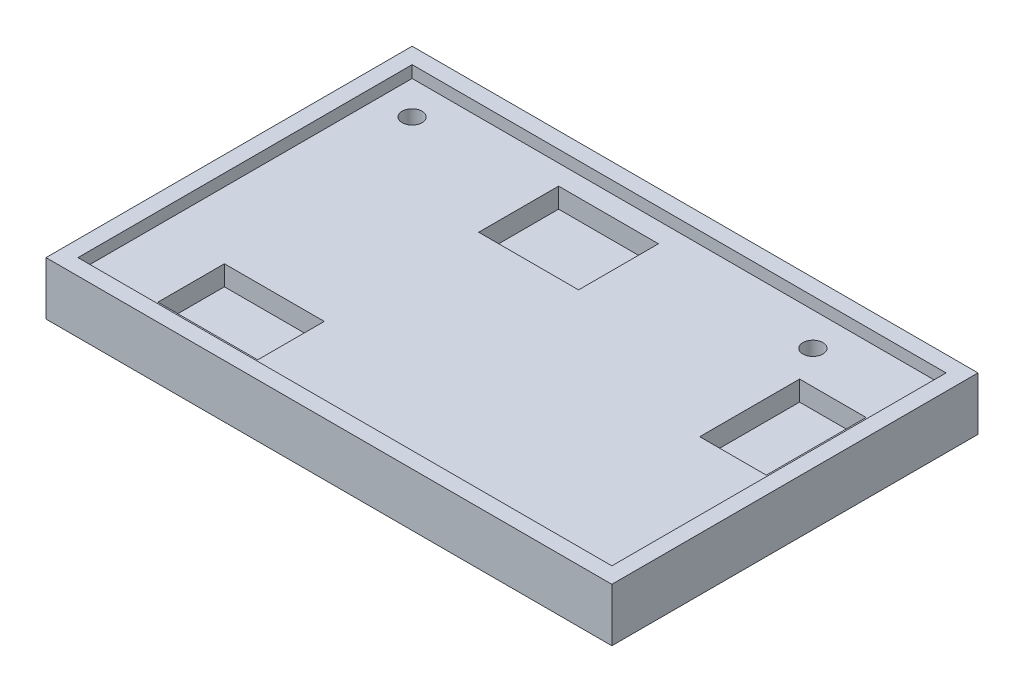
SolidWorks part; units mm, degrees
ref_plane "前视基准面" through (0, 0, 0) normal (0, 0, 1) x (1, 0, 0)
ref_plane "上视基准面" through (0, 0, 0) normal (0, 1, 0) x (1, 0, 0)
ref_plane "右视基准面" through (0, 0, 0) normal (1, 0, 0) x (0, 0, -1)
other "Configuration Table"
sketch "草图2" plane through (0, 0, 0) normal (0, 1, 0) x (1, 0, 0)
  line L0 (-5, -5) -> (-5, 60)
  line L1 (0, 0) -> (85, 0)
  line L2 (0, 0) -> (0, 55)
  line L3 (0, 55) -> (85, 55)
  line L4 (85, 0) -> (85, 55)
  line L5 (-5, 60) -> (90, 60)
  line L6 (90, -5) -> (90, 60)
  line L7 (-5, -5) -> (90, -5)
  dimension "D1" = 5
  dimension "D2" = 55
  dimension "D3" = 85
extrude "凸台-拉伸3" add sketch "草图2" along normal blind 8 contours L2 L1 L4 L3
sketch "草图5" plane through (0, 8, 0) normal (0, 1, 0) x (1, 0, 0)
  line L9 (2.4, 2.4) -> (82.6, 2.4)
  line L10 (82.6, 2.4) -> (82.6, 52.6)
  line L11 (82.6, 52.6) -> (2.4, 52.6)
  line L12 (2.4, 52.6) -> (2.4, 2.4)
  line L13 (2.4, 2.4) -> (82.6, 2.4)
  line L14 (82.6, 2.4) -> (82.6, 52.6)
  line L15 (82.6, 52.6) -> (2.4, 52.6)
  line L16 (2.4, 52.6) -> (2.4, 2.4)
  dimension "D1" = 2.4
extrude "切除-拉伸1" cut sketch "草图5" against normal blind 1.8 contours L13 L14 L15 L16
sketch "草图7" plane through (0, 6.2, 0) normal (0, 1, 0) x (1, 0, 0)
  line L0 (2.4, 52.6) -> (2.4, 2.4) construction
  line L1 (82.6, 52.6) -> (2.4, 52.6) construction
  line L6 (37.5, 42.5) -> (37.5, 50.7498) construction
  line L8 (2.5, 22.5) -> (6.7449, 22.5) construction
  circle A0 centre (7.4, 47.6) radius 1.5
  circle A1 centre (67.6, 47.6) radius 1.5
  circle A2 centre (7.4, -2.6) radius 1.5
  circle A3 centre (67.6, -2.6) radius 1.5
  dimension "D1" = 3
  dimension "D2" = 5
  dimension "D3" = 5
extrude "切除-拉伸4" cut sketch "草图7" against normal blind 2.2
sketch "草图8" plane through (0, 6.2, 0) normal (0, 1, 0) x (1, 0, 0)
  line L0 (2.4, 52.6) -> (2.4, 2.4) construction
  line L1 (12.4, 14.4) -> (27.4, 14.4)
  line L2 (12.4, 14.4) -> (12.4, 4.4)
  line L3 (12.4, 4.4) -> (27.4, 4.4)
  line L4 (27.4, 14.4) -> (27.4, 4.4)
  line L5 (2.4, 2.4) -> (82.6, 2.4) construction
  line L6 (2.4, 2.4) -> (82.6, 2.4) construction
  line L7 (82.6, 52.6) -> (2.4, 52.6) construction
  line L8 (70.6, 42.6) -> (80.6, 42.6)
  line L9 (70.6, 42.6) -> (70.6, 27.6)
  line L10 (70.6, 27.6) -> (80.6, 27.6)
  line L11 (80.6, 42.6) -> (80.6, 27.6)
  line L12 (82.6, 2.4) -> (82.6, 52.6) construction
  line L13 (82.6, 2.4) -> (82.6, 52.6) construction
  line L14 (82.6, 52.6) -> (2.4, 52.6) construction
  line L15 (27.4, 49.6) -> (42.4, 49.6)
  line L16 (27.4, 49.6) -> (27.4, 37.6)
  line L17 (27.4, 37.6) -> (42.4, 37.6)
  line L18 (42.4, 49.6) -> (42.4, 37.6)
  line L19 (2.4, 52.6) -> (2.4, 2.4) construction
  dimension "D1" = 10
  dimension "D2" = 15
  dimension "D3" = 2
  dimension "D4" = 12
  dimension "D5" = 25
  dimension "D6" = 12
  dimension "D7" = 2
  dimension "D8" = 10
  dimension "D9" = 25
  dimension "D10" = 15
  dimension "D11" = 3
  dimension "D12" = 40
extrude "切除-拉伸6" cut sketch "草图8" against normal blind 3
